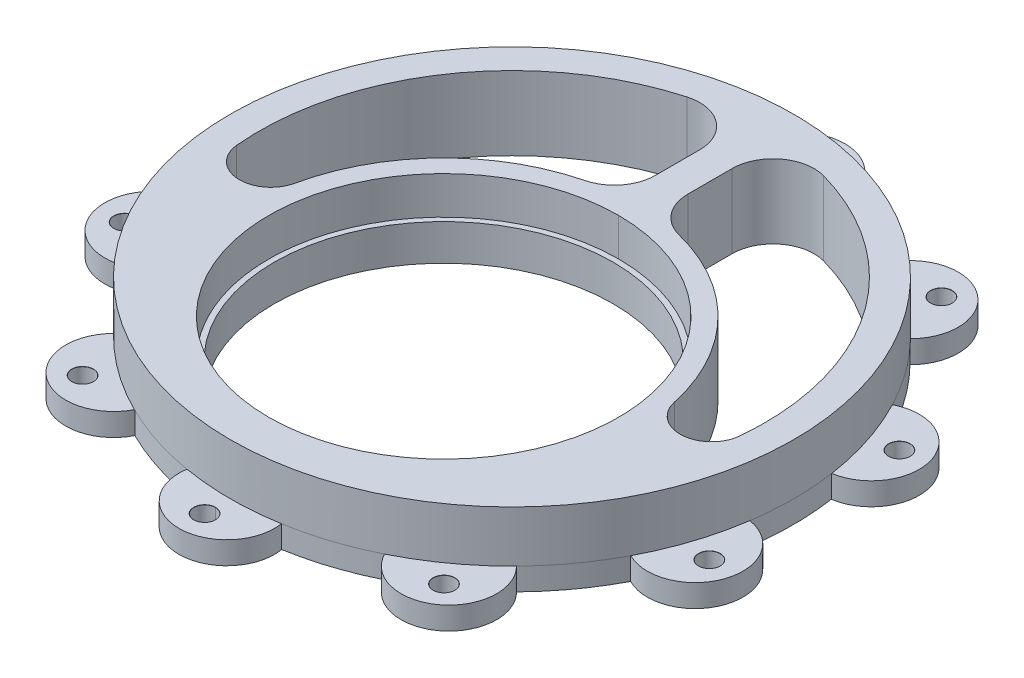
SolidWorks part; units mm, degrees
material "6061-T6 (SS)"
ref_plane "X-Y Datum" through (0, 0, 0) normal (0, 0, 1) x (1, 0, 0)
ref_plane "X-Z Datum" through (0, 0, 0) normal (0, 1, 0) x (1, 0, 0)
ref_plane "Y-Z Datum" through (0, 0, 0) normal (1, 0, 0) x (0, 0, -1)
sketch "Sketch1" plane through (0, 0, 0) normal (0, 1, 0) x (1, 0, 0)
  line L0 (0, 0) -> (0, -12.7) construction
  line L1 (0, -43.0151) -> (0, 43.0151) construction
  line L2 (0, 52.3875) -> (0, 61.9125) construction
  circle A0 centre (0, -12.7) radius 30.988
  circle A1 centre (0, 0) radius 52.3875 construction
  circle A2 centre (0, 0) radius 61.9125
  circle A3 centre (0, 0) radius 57.15 construction
  point P12 (0, 57.15)
  dimension "D2" = 61.976
  dimension "D3" = 104.775
  dimension "D4" = 123.825
  dimension "D5" = 114.3
  dimension "D1" = 12.7
extrude "Slotted-Body Extrude" add sketch "Sketch1" along normal blind 4.191
sketch "Sketch5" plane through (0, 4.191, 0) normal (0, 1, 0) x (1, 0, 0)
  circle A0 centre (0, 0) radius 52.3875 construction
  circle A1 centre (0, 0) radius 52.3875
extrude "Boss-Extrude3" add sketch "Sketch5" along normal blind 9.525
sketch "Sketch6" plane through (0, 0, 0) normal (0, -1, 0) x (1, 0, 0)
  line L0 (0, -79.2756) -> (0, 0) construction
  line L2 (3.014, -37.9067) -> (3.014, -29.6741)
  line L4 (-3.014, -37.9067) -> (-3.014, -29.6741)
  circle A0 centre (0, 12.7) radius 30.988 construction
  circle A1 centre (0, 12.7) radius 30.988 construction
  circle A2 centre (0, 12.7) radius 32.512
  arc A9 (-35.2562, 5.0907) -> (-8.7792, -22.2832) centre (0, 12.7) ccw
  arc A10 (-46.783, 4.406) -> (-12.6921, -45.2435) centre (0, 0) ccw
  arc A11 (-46.783, 4.406) -> (-35.2562, 5.0907) centre (-40.9667, 3.8583) cw
  arc A19 (-3.014, -29.6741) -> (-8.7792, -22.2832) centre (-10.634, -29.6741) ccw
  arc A20 (-3.014, -37.9067) -> (-12.6921, -45.2435) centre (-10.634, -37.9067) cw
  circle A21 centre (0, 0) radius 61.9125 construction
  arc A27 (46.783, 4.406) -> (35.2562, 5.0907) centre (40.9667, 3.8583) ccw
  arc A28 (46.783, 4.406) -> (12.6921, -45.2435) centre (0, 0) cw
  arc A29 (3.014, -37.9067) -> (12.6921, -45.2435) centre (10.634, -37.9067) ccw
  arc A30 (3.014, -29.6741) -> (8.7792, -22.2832) centre (10.634, -29.6741) cw
  arc A31 (35.2562, 5.0907) -> (8.7792, -22.2832) centre (0, 12.7) cw
  point P30 (0, 0)
  point P31 (-3.014, -23.2419)
  point P32 (0, 0)
  point P36 (-3.014, -46.8932)
  dimension "D1" = 65.024
  dimension "D2" = 7.62
  dimension "D3" = 5.842
  dimension "D4" = 46.99
  dimension "D5" = 7.62
  dimension "D6" = 36.068
  dimension "D8" = 8.2326
extrude "Cut-Extrude5" cut sketch "Sketch6" against normal through all
sketch "Sketch8" plane through (0, 0, 0) normal (0, -1, 0) x (1, 0, 0)
  circle A0 centre (0, 12.7) radius 32.512 construction
  circle A1 centre (0, 12.7) radius 32.512
  circle A2 centre (0, 12.7) radius 31.496
  dimension "D1" = 62.992
extrude "Boss-Extrude4" add sketch "Sketch8" against normal blind 6.7 separate body
hole_wizard "Ø4.0mm Dowel Hole2" positions "Sketch9" profile "Sketch10" hole size "Ø4.0" standard "ANSI Metric" end condition through all
sketch "Sketch9" plane through (0, 4.191, 0) normal (0, 1, 0) x (1, 0, 0)
  point P0 (0, 57.15)
sketch "Sketch10" plane through (0, 4.191, -57.15) normal (1, 0, 0) x (0, 0, 1)
  line L0 (0, 0) -> (0, 4.191)
  line L1 (0, 4.191) -> (2, 4.191)
  line L2 (2, 4.191) -> (2, 0.025)
  line L3 (2, 0.025) -> (2.025, 0)
  line L5 (2.025, 0) -> (0, 0)
  line L6 (-2, 0.025) -> (-2.025, 0) construction
  line L11 (0, -6.35) -> (0, 107.95) construction
  dimension "Thru Hole Dia." = 4
  dimension "Thru Hole Depth" = 4.191
  dimension "Near C'Sink Dia." = 4.05
  dimension "Near C'Sink Angle" = 90
pattern_circular "CirPattern1" count 10 over 360 about axis through (0, 0, 0) along (0, 1, 0) of "Ø4.0mm Dowel Hole2"
ref_point "Point1"
ref_plane "Plane1" through (0, 0, 0) normal (1, 0, 0) x (0, 0, -1)
split line "Split Line1"
ref_point "Point4"
ref_point "Point5"
split line "Split Line2"
split line "Split Line3"
sketch "Sketch14" plane through (0, 4.191, 0) normal (0, 1, 0) x (1, 0, 0)
  arc A2 (-8.7727, 51.5833) -> (8.7727, 51.5833) centre (0, 53.0225) cw
  circle A3 centre (0, 0) radius 61.9125 construction
  circle A4 centre (0, 0) radius 52.324 construction
  arc A5 (-8.7727, 51.5833) -> (8.7727, 51.5833) centre (0, 0) cw
  arc A6 (23.2226, 46.8883) -> (37.4172, 36.5753) centre (0, 0) cw
  arc A7 (23.2226, 46.8883) -> (37.4172, 36.5753) centre (31.1658, 42.8961) cw
  arc A8 (46.3477, 24.2835) -> (51.7696, 7.5968) centre (0, 0) cw
  arc A9 (46.3477, 24.2835) -> (51.7696, 7.5968) centre (50.4274, 16.3849) cw
  arc A10 (51.7696, -7.5968) -> (46.3477, -24.2835) centre (0, 0) cw
  arc A11 (51.7696, -7.5968) -> (46.3477, -24.2835) centre (50.4274, -16.3849) cw
  arc A12 (37.4172, -36.5753) -> (23.2226, -46.8883) centre (0, 0) cw
  arc A13 (37.4172, -36.5753) -> (23.2226, -46.8883) centre (31.1658, -42.8961) cw
  arc A14 (8.7727, -51.5833) -> (-8.7727, -51.5833) centre (0, 0) cw
  arc A15 (8.7727, -51.5833) -> (-8.7727, -51.5833) centre (0, -53.0225) cw
  arc A16 (-23.2226, -46.8883) -> (-37.4172, -36.5753) centre (0, 0) cw
  arc A17 (-23.2226, -46.8883) -> (-37.4172, -36.5753) centre (-31.1658, -42.8961) cw
  arc A18 (-46.3477, -24.2835) -> (-51.7696, -7.5968) centre (0, 0) cw
  arc A19 (-46.3477, -24.2835) -> (-51.7696, -7.5968) centre (-50.4274, -16.3849) cw
  arc A20 (-51.7696, 7.5968) -> (-46.3477, 24.2835) centre (0, 0) cw
  arc A21 (-51.7696, 7.5968) -> (-46.3477, 24.2835) centre (-50.4274, 16.3849) cw
  arc A22 (-37.4172, 36.5753) -> (-23.2226, 46.8883) centre (0, 0) cw
  arc A23 (-37.4172, 36.5753) -> (-23.2226, 46.8883) centre (-31.1658, 42.8961) cw
  point P9 (0, 57.15)
  point P10 (0, 61.9125)
  point P41 (0, 0)
  dimension "D1" = 104.648
  dimension "D2" = 8.89
  dimension "D3" = 10
sketch "Sketch15" plane through (0, 4.191, 0) normal (0, 1, 0) x (1, 0, 0)
  arc A0 (-23.2226, 46.8883) -> (-36.3913, 50.0883) centre (-31.1658, 42.8961) ccw
  arc A1 (-23.2226, 46.8883) -> (-37.4172, 36.5753) centre (-31.1658, 42.8961) ccw construction
  arc A2 (-8.7727, 51.5833) -> (-23.2226, 46.8883) centre (0, 0) ccw
  arc A3 (-8.7727, 51.5833) -> (0, 61.9125) centre (0, 53.0225) cw
  arc A4 (8.7727, 51.5833) -> (-8.7727, 51.5833) centre (0, 53.0225) ccw construction
  arc A5 (0, 61.9125) -> (-36.3913, 50.0883) centre (0, 0) ccw
  dimension "D1" = 61.9125
  dimension "D2" = 52.324
extrude "Cut-Extrude9" cut sketch "Sketch15" against normal through all
pattern_circular "CirPattern6" count 10 over 360 about axis through (0, 0, 0) along (0, 1, 0) of "Cut-Extrude9"
